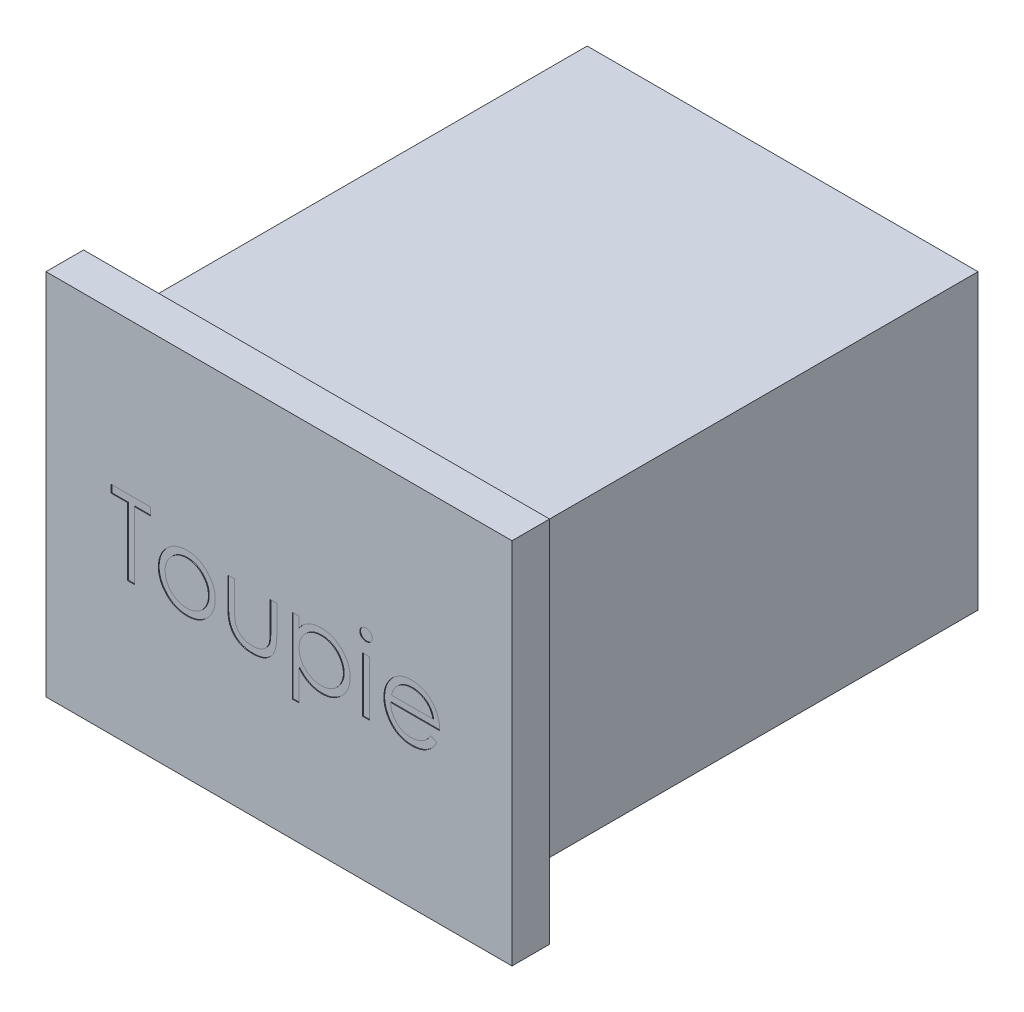
SolidWorks part; units mm, degrees
ref_plane "Front" through (0, 0, 0) normal (0, 0, 1) x (1, 0, 0)
ref_plane "Top" through (0, 0, 0) normal (0, 1, 0) x (1, 0, 0)
ref_plane "Right" through (0, 0, 0) normal (1, 0, 0) x (0, 0, -1)
sketch "Esquisse1" plane through (0, 0, 0) normal (0, 0, 1) x (1, 0, 0)
  line L1 (0, 0) -> (620, 0)
  line L2 (0, 0) -> (0, 490)
  line L3 (0, 490) -> (620, 490)
  line L4 (620, 0) -> (620, 490)
  dimension "D1" = 620
  dimension "D2" = 490
extrude "Boss.-Extru.1" add sketch "Esquisse1" along normal blind 50
sketch "Esquisse2" plane through (0, 0, 0) normal (0, 0, -1) x (-1, 0, 0)
  line L0 (-310, 440) -> (-310, 490) construction
  line L1 (-570, 50) -> (-50, 50)
  line L2 (-570, 50) -> (-570, 440)
  line L3 (-570, 440) -> (-50, 440)
  line L4 (-50, 50) -> (-50, 440)
  line L5 (-620, 490) -> (0, 490) construction
  line L6 (-50, 245) -> (0, 245) construction
  line L7 (0, 490) -> (0, 0) construction
  line L8 (0, 0) -> (-620, 0) construction
  dimension "D1" = 50
extrude "Boss.-Extru.2" add sketch "Esquisse2" along normal blind 620
sketch "Esquisse3" plane through (0, 0, 50) normal (0, 0, 1) x (1, 0, 0)
  text T0 "Toupie" font "Century Gothic" height 100
extrude "Enlèv. mat.-Extru.1" cut sketch "Esquisse3" against normal blind 1
